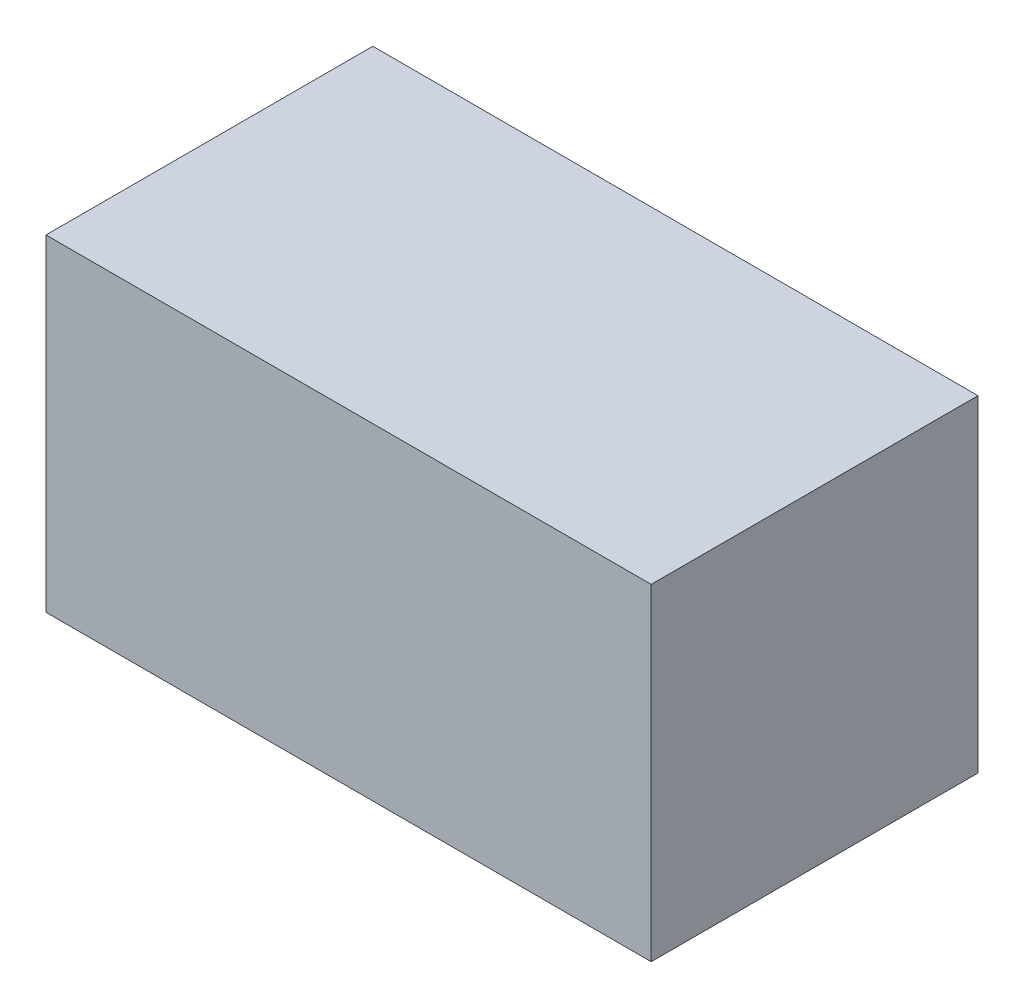
SolidWorks part; units mm, degrees
ref_plane "前视基准面" through (0, 0, 0) normal (0, 0, 1) x (1, 0, 0)
ref_plane "上视基准面" through (0, 0, 0) normal (0, 1, 0) x (1, 0, 0)
ref_plane "右视基准面" through (0, 0, 0) normal (1, 0, 0) x (0, 0, -1)
sketch "草图1" plane through (0, 0, 0) normal (0, 0, 1) x (1, 0, 0)
  line L0 (-1.25, -0.675) -> (-1.25, 0.675)
  line L1 (-1.25, 0.675) -> (1.25, 0.675)
  line L2 (1.25, 0.675) -> (1.25, -0.675)
  line L3 (1.25, -0.675) -> (-1.25, -0.675)
extrude "Component_Outline" add sketch "草图1" along normal blind 1.35 separate body
sketch3d "3D草图1"
  line L0 (0, 0, 0) -> (1, 0, 0)
  line L1 (0, 0, 0) -> (0, 1, 0)
  line L2 (0, 0, 0) -> (0, 0, 1)
  point P0 (0, 0, 0)
